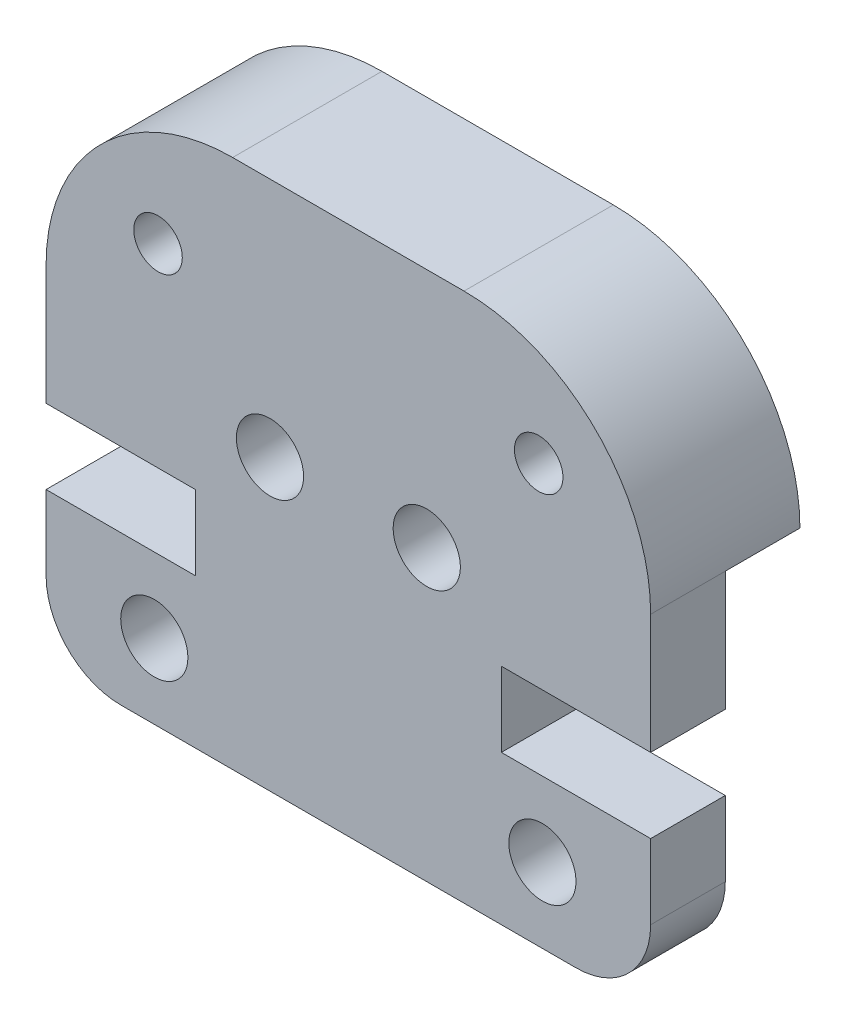
SolidWorks part; units mm, degrees
ref_plane "Front Plane" through (0, 0, 0) normal (0, 0, 1) x (1, 0, 0)
ref_plane "Top Plane" through (0, 0, 0) normal (0, 1, 0) x (1, 0, 0)
ref_plane "Right Plane" through (0, 0, 0) normal (1, 0, 0) x (0, 0, -1)
sketch "Sketch1" plane through (0, 0, 0) normal (0, 0, 1) x (1, 0, 0)
  line L0 (8.1, 14.205) -> (8.1, 0) construction
  line L1 (12.2, 4) -> (16.2, 4)
  line L2 (12.2, 6) -> (12.2, 4)
  line L3 (16.2, 6) -> (12.2, 6)
  line L4 (16.2, 2) -> (16.2, 4)
  line L5 (16.2, 9.205) -> (16.2, 6)
  line L14 (0, 9.205) -> (0, 6)
  line L15 (5, 14.205) -> (11.2, 14.205)
  line L16 (2, 0) -> (14.2, 0)
  line L18 (0, 2) -> (0, 4)
  line L19 (0, 6) -> (4, 6)
  line L21 (4, 6) -> (4, 4)
  line L22 (4, 4) -> (0, 4)
  circle A0 centre (13.3, 2) radius 0.9
  arc A1 (16.2, 2) -> (14.2, 0) centre (14.2, 2) cw
  circle A2 centre (13.2, 11.205) radius 0.65
  arc A3 (11.2, 14.205) -> (16.2, 9.205) centre (11.2, 9.205) cw
  circle A4 centre (10.2, 7.75) radius 0.9
  circle A11 centre (6, 7.75) radius 0.9
  arc A13 (5, 14.205) -> (0, 9.205) centre (5, 9.205) ccw
  circle A15 centre (3, 11.205) radius 0.65
  arc A17 (0, 2) -> (2, 0) centre (2, 2) ccw
  circle A19 centre (2.9, 2) radius 0.9
  dimension "D1" = 1.3
  dimension "D2" = 1.8
  dimension "D3" = 5
  dimension "D4" = 2
  dimension "D5" = 3
  dimension "D6" = 6
  dimension "D7" = 8.1
  dimension "D8" = 7.75
  dimension "D10" = 14.205
  dimension "D9" = 3
extrude "Boss-Extrude1" add sketch "Sketch1" along normal blind 4
sketch "Sketch2" plane through (0, 0, 0) normal (0, 0, -1) x (-1, 0, 0)
  line L0 (0, 0) -> (0, 9.205)
  line L1 (0, 9.205) -> (-16.2, 9.205)
  line L2 (-16.2, 9.205) -> (-16.2, 0)
  line L3 (-16.2, 0) -> (0, 0)
extrude "Cut-Extrude1" cut sketch "Sketch2" against normal blind 2
equation "\"D7@Sketch1\"= \"fingerWidth@parametersSketch@prostheticParameters.SLDPRT\" / 2 'DIP width"
equation "\"D10@Sketch1\"= \"HL@parametersSketch@prostheticParameters.SLDPRT\" * 0.093 - 3 'DIP length - Sil. Sht DIP"
equation "\"D1@Sketch1\"= 1 + \"tol1@parametersSketch@prostheticParameters.SLDPRT\""
equation "\"D2@Sketch1\"= 1.5 + \"tol1@parametersSketch@prostheticParameters.SLDPRT\""
